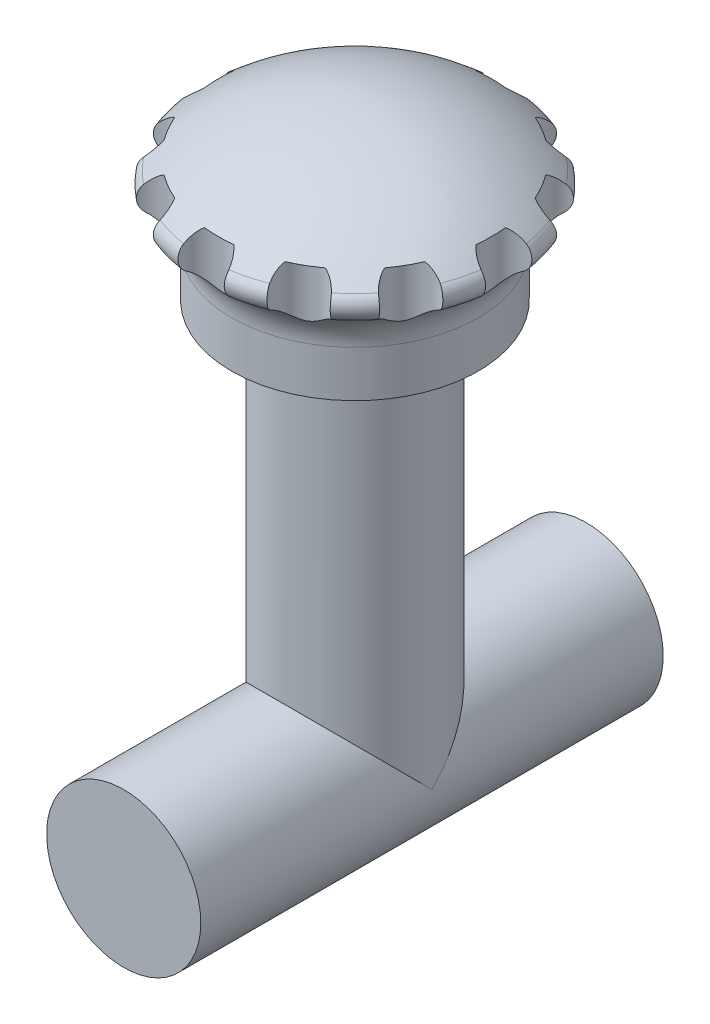
SolidWorks part; units mm, degrees
ref_plane "Front Plane" through (0, 0, 0) normal (0, 0, 1) x (1, 0, 0)
ref_plane "Top Plane" through (0, 0, 0) normal (0, 1, 0) x (1, 0, 0)
ref_plane "Right Plane" through (0, 0, 0) normal (1, 0, 0) x (0, 0, -1)
sketch "Sketch1" plane through (0, 0, 0) normal (0, 0, 1) x (1, 0, 0)
  circle A0 centre (0, 0) radius 5
  dimension "D1" = 10
extrude "Boss-Extrude1" add sketch "Sketch1" against normal blind 30
sketch "Sketch2" plane through (0, 0, 0) normal (0, 1, 0) x (1, 0, 0)
  line L0 (0, 0) -> (0, 30) construction
  line L1 (5, 30) -> (-5, 30) construction
  circle A0 centre (0, 15) radius 5
  dimension "D1" = 10
extrude "Boss-Extrude2" add sketch "Sketch2" along normal blind 25
sketch "Sketch3" plane through (0, 25, 0) normal (0, 1, 0) x (1, 0, 0)
  circle A0 centre (0, 15) radius 5 construction
  circle A1 centre (0, 15) radius 5
  circle A2 centre (0, 15) radius 8
  circle M3 centre (0, 15) radius 5
  dimension "D1" = 3
extrude "Boss-Extrude3" add sketch "Sketch3" along normal blind 3 contours M3 | A2 M3
sketch "Sketch5" plane through (0, 0, 0) normal (1, 0, 0) x (0, 0, -1)
  line L0 (15, 25) -> (15, 37.0046) construction
  line L1 (10, 25) -> (20, 25) construction
  line L2 (15, 28) -> (23, 28)
  line L3 (23, 28) -> (7, 28) construction
  line L4 (23, 28) -> (23, 25) construction
  line L5 (15, 36) -> (26, 36) construction
  line L6 (15, 36) -> (15, 28)
  arc A0 (23, 28) -> (24.5682, 30.6363) centre (26, 28) cw
  arc A1 (15, 36) -> (24.7594, 32.2588) centre (15, 21.4) cw
  arc A2 (24.5682, 30.6363) -> (24.7594, 32.2588) centre (24.091, 31.5151) ccw
  point P18 (26, 31)
  dimension "D1" = 3
  dimension "D4" = 1
  dimension "D2" = 11
  dimension "D3" = 8
revolve "Revolve1" add sketch "Sketch5" angle 360 about L6
ref_plane "Plane1" through (0, 28, 0) normal (0, 1, 0) x (1, 0, 0)
sketch "Sketch6" plane through (0, 28, 0) normal (0, 1, 0) x (1, 0, 0)
  line L0 (0, 0) -> (0, 25.091) construction
  circle A0 centre (0, 15) radius 10.091 construction
  arc A1 (-6.2884, 22.892) -> (-7.892, 21.2884) centre (0, 15) ccw
  arc A2 (-1.5, 24.9789) -> (1.5, 24.9789) centre (0, 24.9705) ccw
  arc A3 (3.6904, 24.3919) -> (6.2884, 22.892) centre (4.9852, 23.6347) ccw
  arc A4 (7.892, 21.2884) -> (9.3919, 18.6904) centre (8.6347, 19.9852) ccw
  arc A5 (9.9789, 16.5) -> (9.9789, 13.5) centre (9.9705, 15) ccw
  arc A6 (9.3919, 11.3096) -> (7.892, 8.7116) centre (8.6347, 10.0148) ccw
  arc A7 (6.2884, 7.108) -> (3.6904, 5.6081) centre (4.9852, 6.3653) ccw
  arc A8 (1.5, 5.0211) -> (-1.5, 5.0211) centre (0, 5.0295) ccw
  arc A9 (-3.6904, 5.6081) -> (-6.2884, 7.108) centre (-4.9852, 6.3653) ccw
  arc A10 (-7.892, 8.7116) -> (-9.3919, 11.3096) centre (-8.6347, 10.0148) ccw
  arc A11 (-9.9789, 13.5) -> (-9.9789, 16.5) centre (-9.9705, 15) ccw
  arc A12 (-9.3919, 18.6904) -> (-7.892, 21.2884) centre (-8.6347, 19.9852) ccw
  arc A13 (-6.2884, 22.892) -> (-3.6904, 24.3919) centre (-4.9852, 23.6347) ccw
  arc A15 (3.6904, 24.3919) -> (1.5, 24.9789) centre (0, 15) ccw
  arc A16 (7.892, 21.2884) -> (6.2884, 22.892) centre (0, 15) ccw
  arc A17 (9.9789, 16.5) -> (9.3919, 18.6904) centre (0, 15) ccw
  arc A18 (9.3919, 11.3096) -> (9.9789, 13.5) centre (0, 15) ccw
  arc A19 (6.2884, 7.108) -> (7.892, 8.7116) centre (0, 15) ccw
  arc A20 (1.5, 5.0211) -> (3.6904, 5.6081) centre (0, 15) ccw
  arc A21 (-3.6904, 5.6081) -> (-1.5, 5.0211) centre (0, 15) ccw
  arc A22 (-7.892, 8.7116) -> (-6.2884, 7.108) centre (0, 15) ccw
  arc A23 (-9.9789, 13.5) -> (-9.3919, 11.3096) centre (0, 15) ccw
  arc A24 (-9.3919, 18.6904) -> (-9.9789, 16.5) centre (0, 15) ccw
  arc A25 (-3.6904, 24.3919) -> (-1.5, 24.9789) centre (0, 15) ccw
  point P9 (0, 23.4705)
  point P45 (0, 15)
  dimension "D1" = 1.5
  dimension "D2" = 24.9705
  dimension "D3" = 12
extrude "Cut-Extrude3" cut sketch "Sketch6" against normal mid plane 10 contours A12 A25
pattern_circular "CirPattern1" count 12 over 360 about axis through (0, 0, -15) along (0, 1, 0) of "Cut-Extrude3"
